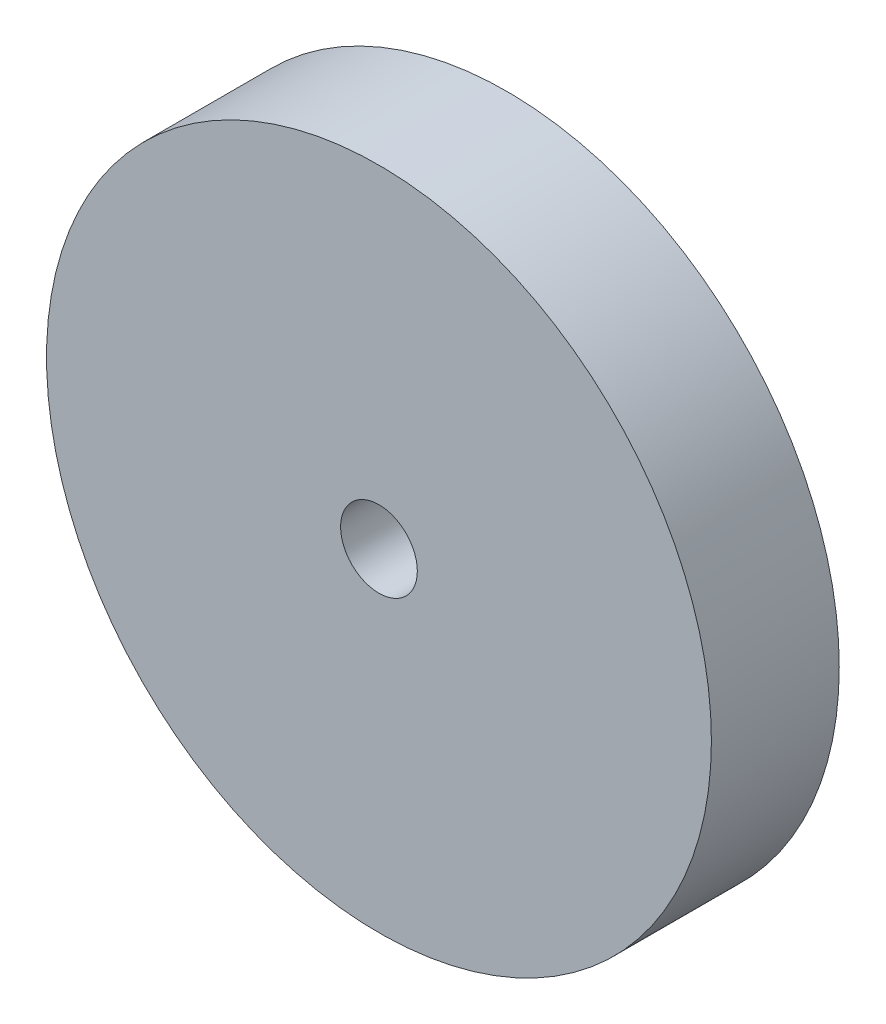
SolidWorks part; units mm, degrees
ref_plane "Plan de face" through (0, 0, 0) normal (0, 0, 1) x (1, 0, 0)
ref_plane "Plan de dessus" through (0, 0, 0) normal (0, 1, 0) x (1, 0, 0)
ref_plane "Plan de droite" through (0, 0, 0) normal (1, 0, 0) x (0, 0, -1)
sketch "Esquisse1" plane through (0, 0, 0) normal (0, 0, 1) x (1, 0, 0)
  circle A0 centre (0, 0) radius 3
  circle A1 centre (0, 0) radius 26
  dimension "D1" = 52
  dimension "D2" = 6
extrude "Boss.-Extru.1" add sketch "Esquisse1" along normal blind 10
